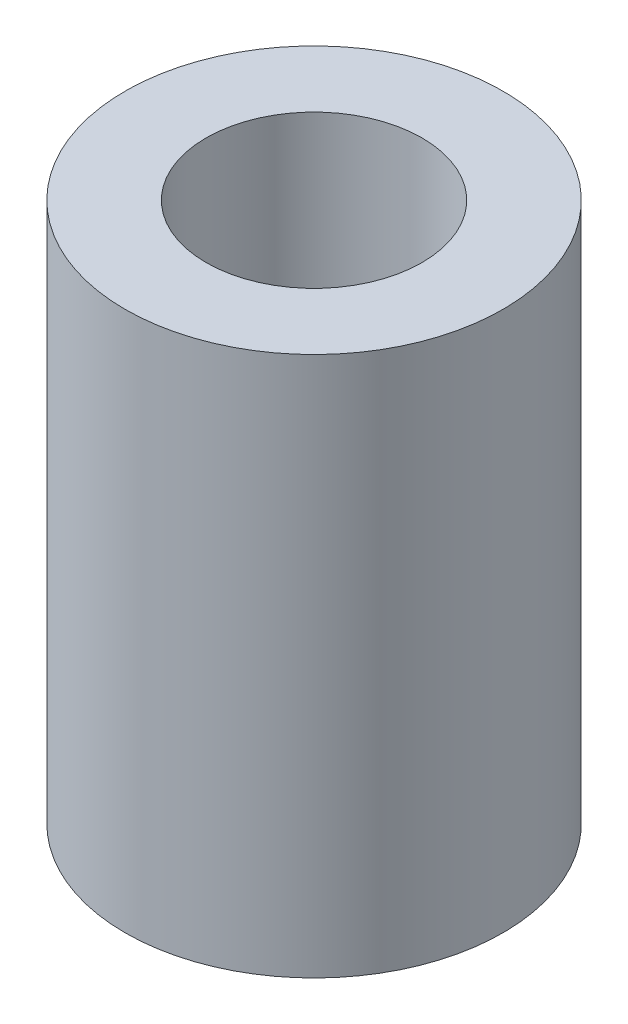
SolidWorks part; units mm, degrees
ref_plane "Спереди" through (0, 0, 0) normal (0, 0, 1) x (1, 0, 0)
ref_plane "Сверху" through (0, 0, 0) normal (0, 1, 0) x (1, 0, 0)
ref_plane "Справа" through (0, 0, 0) normal (1, 0, 0) x (0, 0, -1)
sketch "Эскиз1" plane through (0, 0, 0) normal (0, 1, 0) x (1, 0, 0)
  circle A0 centre (0, 0) radius 2
  circle A1 centre (0, 0) radius 3.5
  dimension "D1" = 4
  dimension "D2" = 7
extrude "Основа" add sketch "Эскиз1" along normal blind 10
